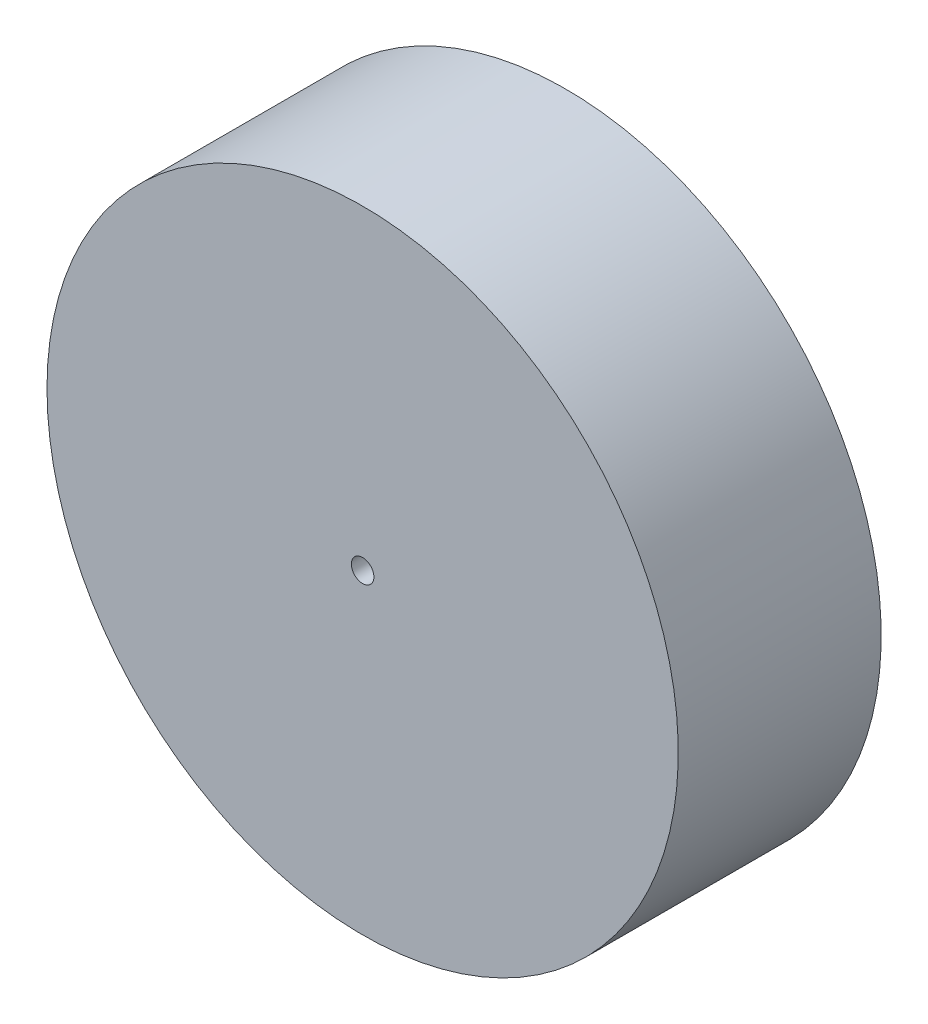
SolidWorks part; units mm, degrees
ref_plane "Front Plane" through (0, 0, 0) normal (0, 0, 1) x (1, 0, 0)
ref_plane "Top Plane" through (0, 0, 0) normal (0, 1, 0) x (1, 0, 0)
ref_plane "Right Plane" through (0, 0, 0) normal (1, 0, 0) x (0, 0, -1)
sketch "Sketch1" plane through (0, 0, 0) normal (0, 0, 1) x (1, 0, 0)
  circle A0 centre (0, 0) radius 70
  dimension "D1" = 140
extrude "Boss-Extrude1" add sketch "Sketch1" along normal blind 45
sketch "Sketch2" plane through (0, 0, 45) normal (0, 0, 1) x (1, 0, 0)
  circle A0 centre (0, 0) radius 2.5
  dimension "D1" = 5
extrude "Cut-Extrude1" cut sketch "Sketch2" against normal blind 20
